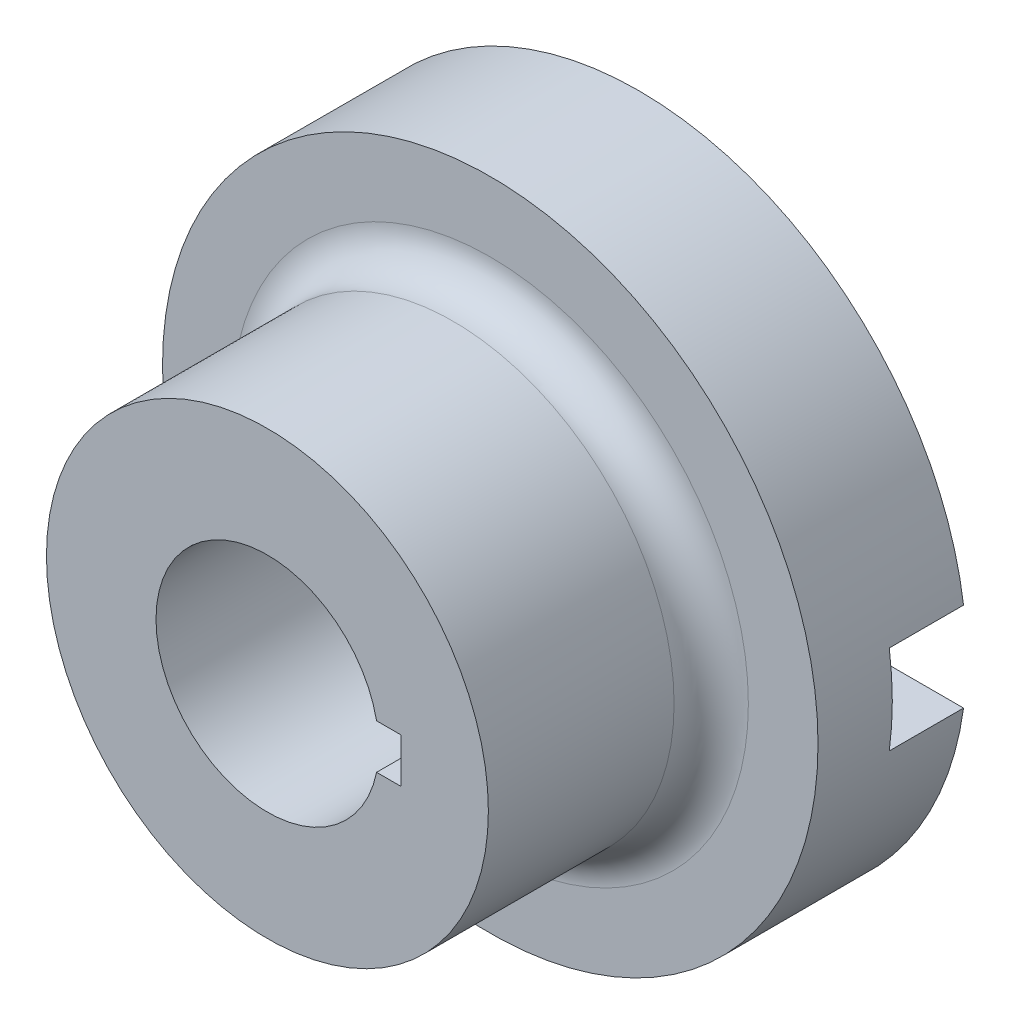
SolidWorks part; units mm, degrees
ref_plane "Front Plane" through (0, 0, 0) normal (0, 0, 1) x (1, 0, 0)
ref_plane "Top Plane" through (0, 0, 0) normal (0, 1, 0) x (1, 0, 0)
ref_plane "Right Plane" through (0, 0, 0) normal (1, 0, 0) x (0, 0, -1)
sketch "Sketch1" plane through (0, 0, 0) normal (1, 0, 0) x (0, 0, -1)
  line L0 (0, 15) -> (0, 44.1244)
  line L1 (0, 44.1244) -> (-20, 44.1244)
  line L2 (-20, 44.1244) -> (-20, 29.7465)
  line L3 (-20, 29.7465) -> (-50, 29.7465)
  line L4 (-50, 29.7465) -> (-50, 15)
  line L5 (-50, 15) -> (0, 15)
  line L6 (0, 0) -> (-50, 0) construction
  dimension "D1" = 50
  dimension "D2" = 20
  dimension "D3" = 15
revolve "Revolve1" add sketch "Sketch1" angle 360 about L6
sketch "Sketch2" plane through (0, 0, 0) normal (0, 0, -1) x (-1, 0, 0)
  line L1 (-59.1574, 6) -> (59.1574, 6)
  line L2 (-59.1574, 6) -> (-59.1574, -6)
  line L3 (-59.1574, -6) -> (59.1574, -6)
  line L4 (59.1574, 6) -> (59.1574, -6)
  line L5 (-59.1574, 6) -> (59.1574, -6) construction
  line L6 (-59.1574, -6) -> (59.1574, 6) construction
  point P0 (0, 0)
  dimension "D1" = 12
extrude "Cut-Extrude1" cut sketch "Sketch2" against normal blind 10
sketch "Sketch3" plane through (0, 0, 50) normal (0, 0, 1) x (1, 0, 0)
  line L0 (0, 0) -> (55.6863, 0) construction
  line L1 (14, 3) -> (18, 3)
  line L2 (14, 3) -> (14, -3)
  line L3 (14, -3) -> (18, -3)
  line L4 (18, 3) -> (18, -3)
  dimension "D1" = 18
  dimension "D2" = 14
  dimension "D3" = 6
extrude "Cut-Extrude2" cut sketch "Sketch3" against normal through all
fillet "Fillet1" radius 5 1 edges at (-29.7465, 0, 20)
